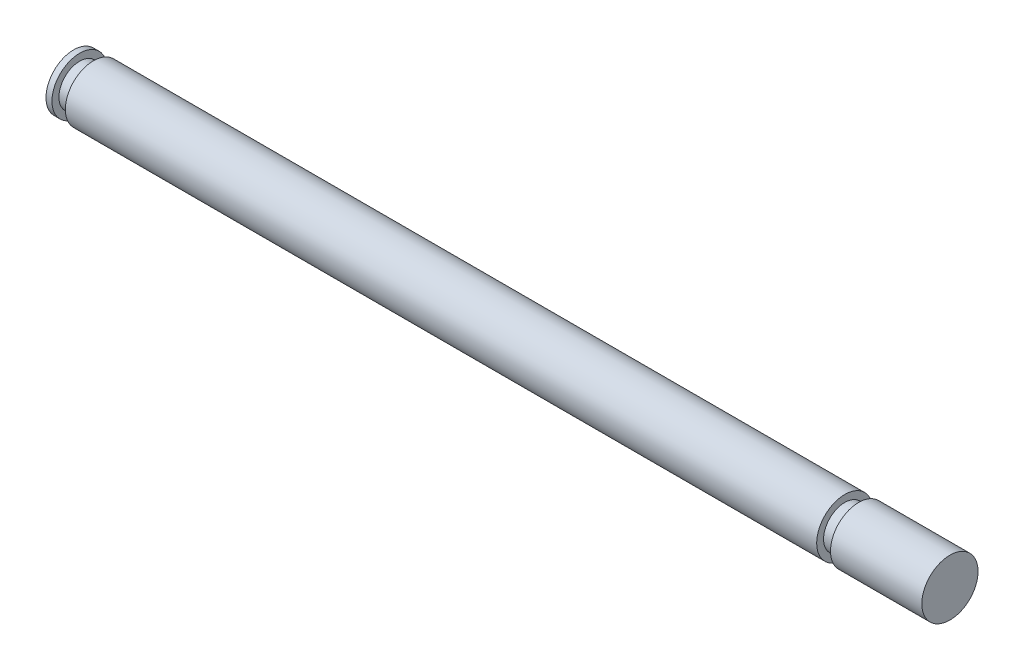
SolidWorks part; units mm, degrees
ref_plane "Front Plane" through (0, 0, 0) normal (0, 0, 1) x (1, 0, 0)
ref_plane "Top Plane" through (0, 0, 0) normal (0, 1, 0) x (1, 0, 0)
ref_plane "Right Plane" through (0, 0, 0) normal (1, 0, 0) x (0, 0, -1)
sketch "Sketch1" plane through (0, 0, 0) normal (0, 0, 1) x (1, 0, 0)
  line L0 (0, 0) -> (0, 50)
  line L1 (0, 50) -> (10.8, 50)
  line L2 (10.8, 50) -> (10.8, 37.5)
  line L3 (10.8, 37.5) -> (35.8, 37.5)
  line L4 (35.8, 37.5) -> (35.8, 50.8318)
  line L5 (0, 0) -> (1583, 0)
  line L6 (1583, 0) -> (1583, 50.8318)
  line L7 (1583, 50.8318) -> (1418.1, 50.8318)
  line L8 (1418.1, 50.8318) -> (1418.1, 38.3318)
  line L9 (1418.1, 38.3318) -> (1393.1, 38.3318)
  line L10 (1393.1, 38.3318) -> (1393.1, 50.8318)
  line L11 (1393.1, 50.8318) -> (35.8, 50.8318)
  dimension "D1" = 50
  dimension "D2" = 10.8
  dimension "D3" = 12.5
  dimension "D4" = 25
  dimension "D5" = 1583
  dimension "D6" = 164.9
  dimension "D7" = 12.5
  dimension "D8" = 25
revolve "Revolve1" add sketch "Sketch1" angle 360 about L5
